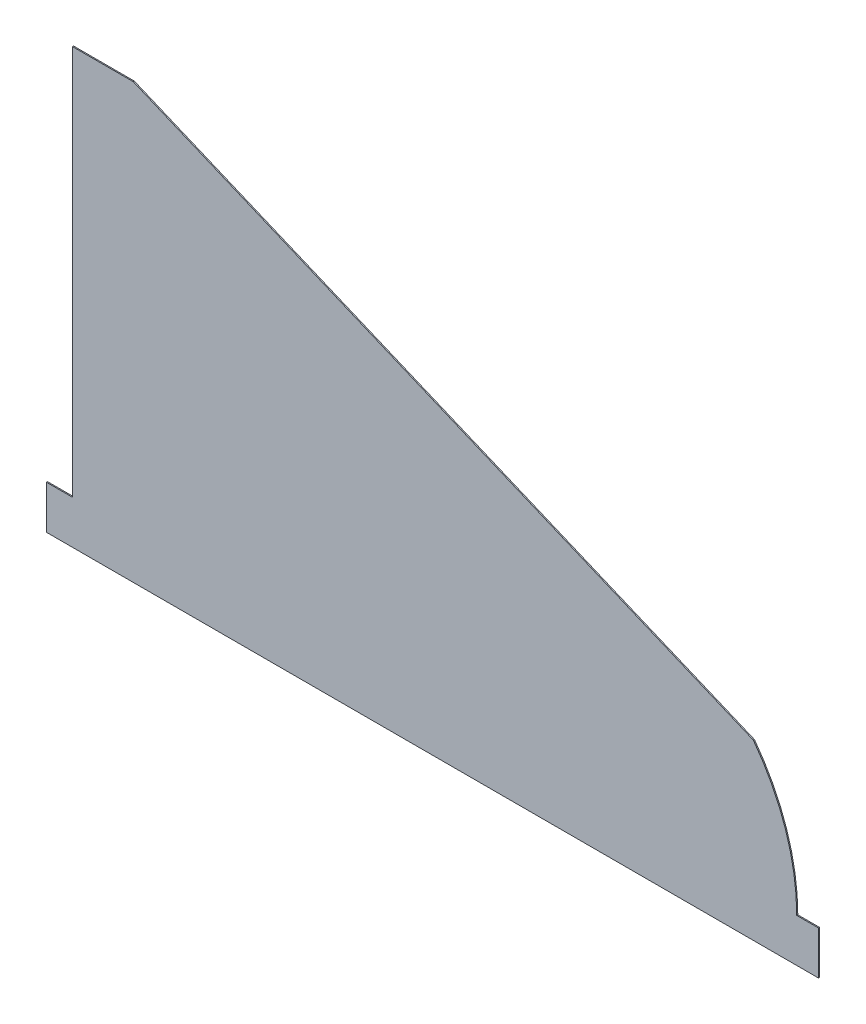
SolidWorks part; units mm, degrees
material "Hexcel AS4C (3000 Filaments)"
ref_plane "Front Plane" through (0, 0, 0) normal (0, 0, 1) x (1, 0, 0)
ref_plane "Top Plane" through (0, 0, 0) normal (0, 1, 0) x (1, 0, 0)
ref_plane "Right Plane" through (0, 0, 0) normal (1, 0, 0) x (0, 0, -1)
sketch "Sketch1" plane through (0, 0, 0) normal (0, 0, 1) x (1, 0, 0)
  line L0 (0, 0) -> (168, 0)
  line L1 (0, 10) -> (-5, 10)
  line L2 (158, 40) -> (15, 100)
  line L3 (15, 100) -> (0, 100)
  line L4 (0, 100) -> (0, 10)
  line L5 (-5, 10) -> (-5, 0)
  line L6 (168, 0) -> (173, 0)
  line L7 (173, 0) -> (173, 10)
  line L8 (173, 10) -> (168, 10)
  line L9 (-5, 0) -> (0, 0)
  arc A0 (168, 10) -> (158, 40) centre (118, 10) ccw
  dimension "D7" = 5
  dimension "D1" = 168
  dimension "D2" = 10
  dimension "D3" = 100
  dimension "D4" = 15
  dimension "D5" = 5
  dimension "D6" = 10
  dimension "D8" = 10
  dimension "D9" = 40
extrude "Boss-Extrude1" add sketch "Sketch1" along normal mid plane 0.25
sketch "Sketch2" plane through (0, 0, 0.125) normal (0, 0, 1) x (1, 0, 0)
  line L0 (0, 10) -> (-5, 10) construction
  line L1 (0, 10) -> (1, 10)
  line L2 (0, 10) -> (0, 100)
  line L3 (0, 100) -> (1, 100)
  line L4 (1, 10) -> (1, 100)
  line L5 (0, 100) -> (0, 10) construction
  line L6 (15, 100) -> (0, 100) construction
  dimension "D1" = 1
extrude "Cut-Extrude1" cut sketch "Sketch2" against normal through all
